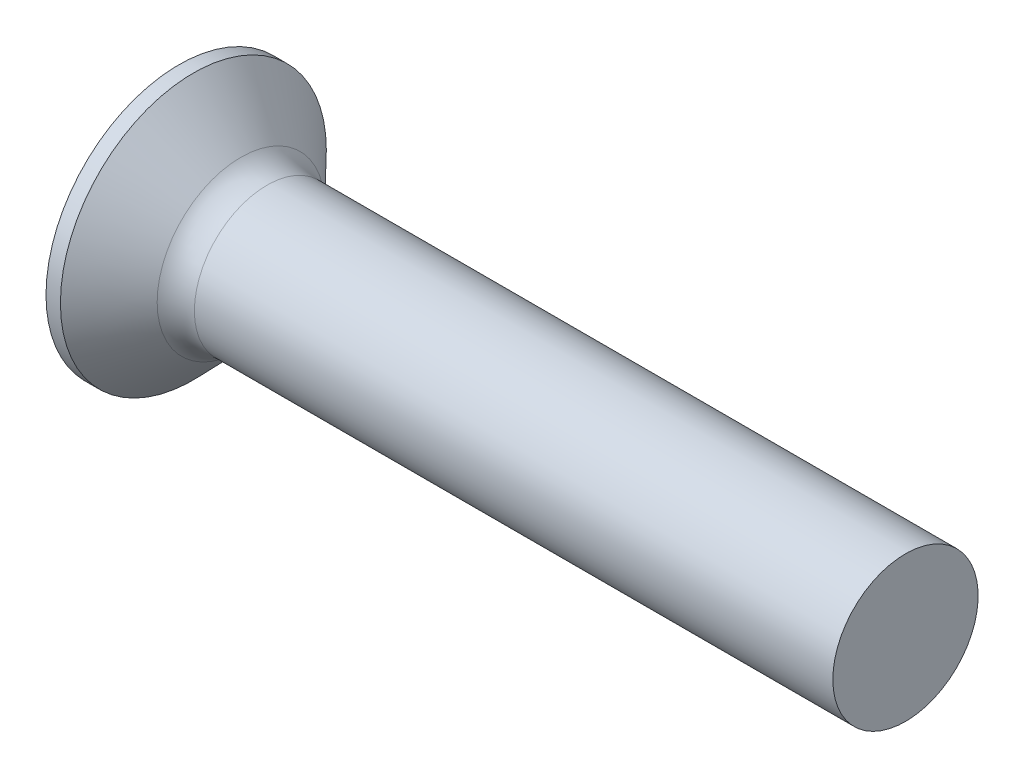
SolidWorks part; units mm, degrees
ref_plane "Plane1" through (0, 0, 0) normal (0, 0, 1) x (1, 0, 0)
ref_plane "Plane2" through (0, 0, 0) normal (0, 1, 0) x (1, 0, 0)
ref_plane "Plane3" through (0, 0, 0) normal (1, 0, 0) x (0, 0, -1)
sketch "BodySke" plane through (0, 0, 0) normal (0, 0, 1) x (1, 0, 0)
  line L0 (0, 0) -> (52.3, 0)
  line L1 (52.3, 0) -> (52.3, 5)
  line L2 (52.3, 5) -> (7.3, 5)
  line L3 (3.2924, -9.15) -> (7.3, -5) construction
  line L4 (-15.875, 0) -> (82.55, 0) construction
  line L5 (3.2924, 9.15) -> (7.3, 5)
  line L6 (8.8, 8.175) -> (8.8, -7.7) construction
  line L7 (2.3, 2.7793) -> (2.3, -13.0957) construction
  line L8 (3.2924, 9.15) -> (2.3, 9.15)
  arc A0 (0, 0) -> (2.3, 9.15) centre (19.3505, 0) cw
  dimension "Head_ang" = 92
  dimension "Diameter" = 10
  dimension "Advance" = 1.5
  dimension "Thread_nom" = 50
  dimension "Oval_ht" = 2.3
  dimension "Side_ht" = 5
  dimension "Head_dia" = 18.3
  dimension "Length" = 50
revolve "Base-Revolve" add sketch "BodySke" angle 360 about L4
cosmetic thread "ThreadCosmetic" [suppressed] parameters "Thread_length"=43.5, "Thread_minor"=8.344
fillet "Fillet1" radius 2.5 1 edges at (7.3, 0, 5)
sketch "Sketch3" plane through (0, 0, 0) normal (1, 0, 0) x (0, 0, -1)
  line L0 (1.08, -5.15) -> (-1.08, -5.15)
  line L1 (1.08, -5.15) -> (1.08, 5.15)
  line L2 (-1.08, 5.15) -> (1.08, 5.15)
  line L3 (-1.08, 5.15) -> (-1.08, -5.15)
  dimension "Cross_width" = 2.16
  dimension "D1" = 1.08
  dimension "Cross_dia" = 10.3
  dimension "D2" = 5.15
ref_plane "Plane4" through (6.05, 0, 0) normal (1, 0, 0) x (0, 0, -1)
sketch "Sketch4" plane through (6.05, 0, 0) normal (1, 0, 0) x (0, 0, -1)
  line L0 (1.08, -2.1336) -> (-1.08, -2.1336)
  line L1 (1.08, -2.1336) -> (1.08, 2.1336)
  line L2 (-1.08, 2.1336) -> (1.08, 2.1336)
  line L3 (-1.08, 2.1336) -> (-1.08, -2.1336)
  dimension "D1" = 2.16
  dimension "D2" = 4.2672
  dimension "D3" = 1.08
  dimension "D4" = 2.1336
loft "Recess" cut profiles "Sketch3", "Sketch4"
pattern_circular "RecPat" count 2 every 90 about axis through (0, 0, 0) along (1, 0, 0) of "Recess"
sketch "RecCorSke" plane through (0, 0, 0) normal (0, 0, 1) x (1, 0, 0)
  line L0 (-3.175, 0) -> (15.875, 0) construction
  line L2 (0, 0) -> (0, 2.3536)
  line L3 (0, 2.3536) -> (6.05, 1.9305)
  line L4 (6.05, 1.9305) -> (6.6773, 0)
  line L5 (6.6773, 0) -> (0, 0)
  dimension "Diameter" = 3.861
  dimension "Depth" = 6.05
  dimension "Draft_angle" = 4
  dimension "Bottom_angle" = 18
revolve "RecessCore" cut sketch "RecCorSke" angle 360 about L0
sketch "ThdSchSke" plane through (0, 0, 0) normal (0, 0, 1) x (1, 0, 0)
  line L0 (8.8, -4.172) -> (8.2202, -5)
  line L1 (8.8, -4.172) -> (9.3798, -5)
  line L2 (9.3798, -5) -> (9.3798, -6.25)
  line L3 (-3.175, 0) -> (5.1513, 0) construction
  line L5 (9.3798, -6.25) -> (8.2202, -6.25)
  line L6 (8.2202, -6.25) -> (8.2202, -5)
  dimension "Diameter" = 10
  dimension "SideAngle" = 55
  dimension "VeeAngle" = 70
  dimension "Thread_minor" = 8.344
  dimension "Overcut" = 12.5
  dimension "Start" = 8.8
revolve "ThreadSchematic" [suppressed] cut sketch "ThdSchSke" angle 360 about L3
pattern_linear "ThdSchPat" [suppressed]
equation "\"D1@Sketch3\" = \"Cross_width@Sketch3\" / 2"
equation "\"D2@Sketch3\" = \"Cross_dia@Sketch3\" / 2"
equation "\"Depth@RecCorSke\" = \"Cross_depth@Plane4\""
equation "\"D1@Sketch4\" = \"Cross_width@Sketch3\""
equation "\"D2@Sketch4\" = \"Cross_dia@Sketch3\" - 2.0 * \"Cross_depth@Plane4\" * tan(26.5  * 0.017453292)"
equation "\"D3@Sketch4\" = \"D1@Sketch4\" / 2"
equation "\"D4@Sketch4\" = \"D2@Sketch4\" / 2"
equation "\"Thread_length@ThreadCosmetic\" = ((sgn( (\"Length@BodySke\" - \"Advance@BodySke\" - \"Side_ht@BodySke\" ) - \"Thread_nom@BodySke\" )-1)*( (\"Length@BodySke\" - \"Advance@BodySke\" - \"Side_ht@BodySke\" ) - \"Thread_nom@BodySke\" ))/-2+ \"Thread_nom@BodySke\""
equation "\"Thread_minor@ThdSchSke\" = \"Thread_minor@ThreadCosmetic\""
equation "\"Diameter@ThdSchSke\" = \"Diameter@BodySke\""
equation "\"Overcut@ThdSchSke\" = \"Diameter@BodySke\" * 1.25"
equation "\"Start@ThdSchSke\" = \"Oval_ht@BodySke\" + \"Length@BodySke\" - \"Thread_length@ThreadCosmetic\"  '---Countersunk---"
equation "\"Num_threads@ThdSchPat\" = int( \"Thread_length@ThreadCosmetic\" / \"Advance@BodySke\" + 0.999 )  + 1"
equation "\"Advance@ThdSchPat\" = \"Thread_length@ThreadCosmetic\" /  (\"Num_threads@ThdSchPat\" - 1) 'relax it"
